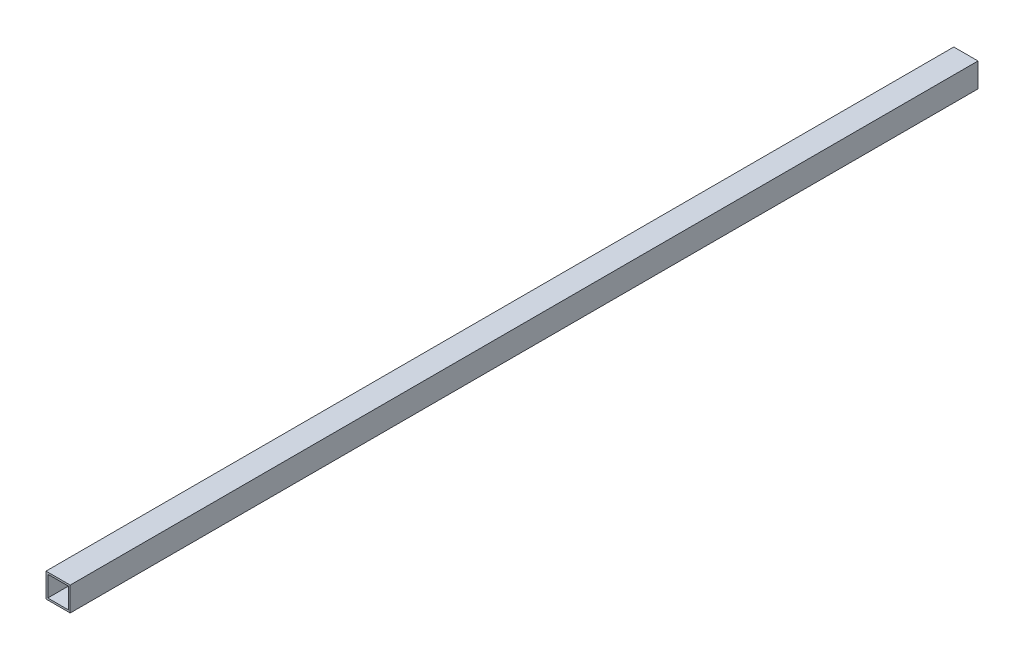
SolidWorks part; units mm, degrees
ref_plane "Front Plane" through (0, 0, 0) normal (0, 0, 1) x (1, 0, 0)
ref_plane "Top Plane" through (0, 0, 0) normal (0, 1, 0) x (1, 0, 0)
ref_plane "Right Plane" through (0, 0, 0) normal (1, 0, 0) x (0, 0, -1)
sketch "Sketch1" plane through (0, 0, 0) normal (0, 0, 1) x (1, 0, 0)
  line L1 (-20, 20) -> (20, 20)
  line L2 (-20, 20) -> (-20, -20)
  line L3 (-20, -20) -> (20, -20)
  line L4 (20, 20) -> (20, -20)
  line L5 (-20, 20) -> (20, -20) construction
  line L6 (-20, -20) -> (20, 20) construction
  point P0 (0, 0)
  dimension "D1" = 40
  dimension "D2" = 40
extrude "Boss-Extrude1" add sketch "Sketch1" along normal blind 1500
sketch "Sketch2" plane through (0, 0, 0) normal (0, 0, -1) x (-1, 0, 0)
  line L1 (-17, 17) -> (17, 17)
  line L2 (-17, 17) -> (-17, -17)
  line L3 (-17, -17) -> (17, -17)
  line L4 (17, 17) -> (17, -17)
  line L5 (-17, 17) -> (17, -17) construction
  line L6 (-17, -17) -> (17, 17) construction
  point P0 (0, 0)
  dimension "D1" = 34
  dimension "D2" = 34
extrude "Cut-Extrude1" cut sketch "Sketch2" against normal blind 1500
